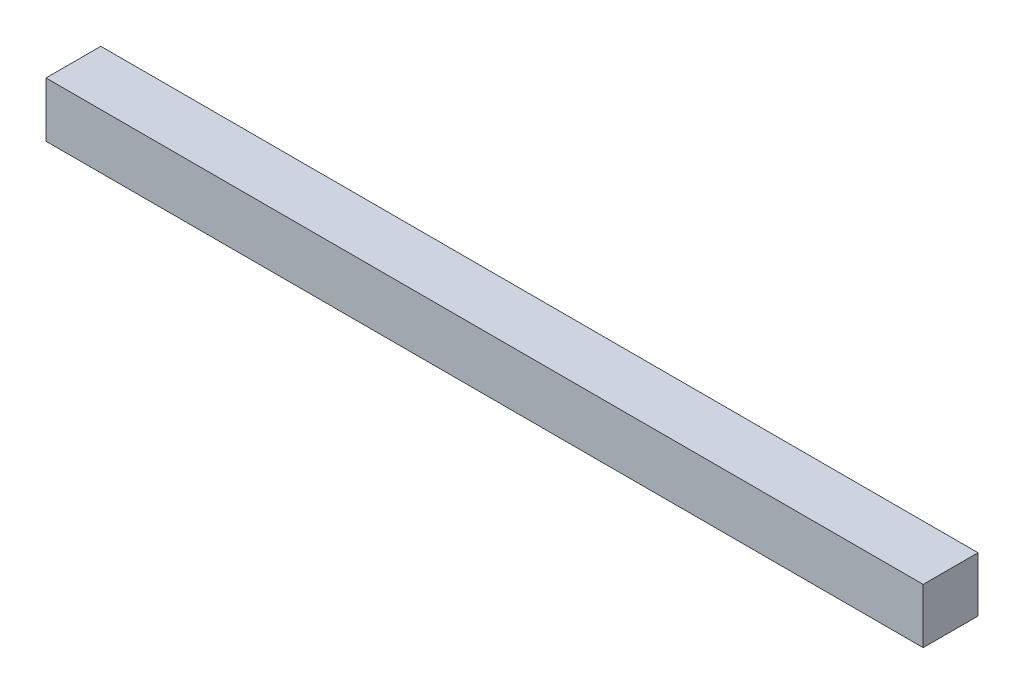
SolidWorks part; units mm, degrees
ref_plane "Front Plane" through (0, 0, 0) normal (0, 0, 1) x (1, 0, 0)
ref_plane "Top Plane" through (0, 0, 0) normal (0, 1, 0) x (1, 0, 0)
ref_plane "Right Plane" through (0, 0, 0) normal (1, 0, 0) x (0, 0, -1)
sketch "Belt Drive Axle" plane through (0, 0, 0) normal (0, 1, 0) x (1, 0, 0)
  line L1 (-50.8, -3.175) -> (50.8, -3.175)
  line L2 (-50.8, -3.175) -> (-50.8, 3.175)
  line L3 (-50.8, 3.175) -> (50.8, 3.175)
  line L4 (50.8, -3.175) -> (50.8, 3.175)
  line L5 (-50.8, -3.175) -> (50.8, 3.175) construction
  line L6 (-50.8, 3.175) -> (50.8, -3.175) construction
  point P0 (0, 0)
  dimension "D1" = 6.35
  dimension "D2" = 101.6
extrude "Boss-Extrude1" add sketch "Belt Drive Axle" along normal blind 6.35
equation "\"Ball Diameter\"= 1.75in"
equation "\"Sheet Thickness\"= 0.25in"
equation "\"Screw Diameter\"= .17in"
equation "\"Robot Diameter\"= 14in"
equation "\"Castor Screw Diameter\"= 0.22in"
equation "\"Wheel Diameter\" = 4in"
equation "\"Nut Diameter\" = 8.4mm"
equation "\"Nut Height\" = 2.9mm"
equation "\"Screw Height\" = 0.55in"
equation "\"Pulley Diameter\" = 1in"
equation "\"Reactor Height\" = 14in"
equation "\"D1@Belt Drive Axle\"=\"Sheet Thickness\""
equation "\"Elevator Height\" = 11.5in"
equation "\"Elevator Width\" = \"Ball Diameter\" + 0.25in"
equation "\"Elevator Axle Length\" = \"Elevator Width\" + 8*\"Sheet Thickness\""
equation "\"D2@Belt Drive Axle\"=\"Elevator Axle Length\""
equation "\"D1@Boss-Extrude1\"=\"Sheet Thickness\""
